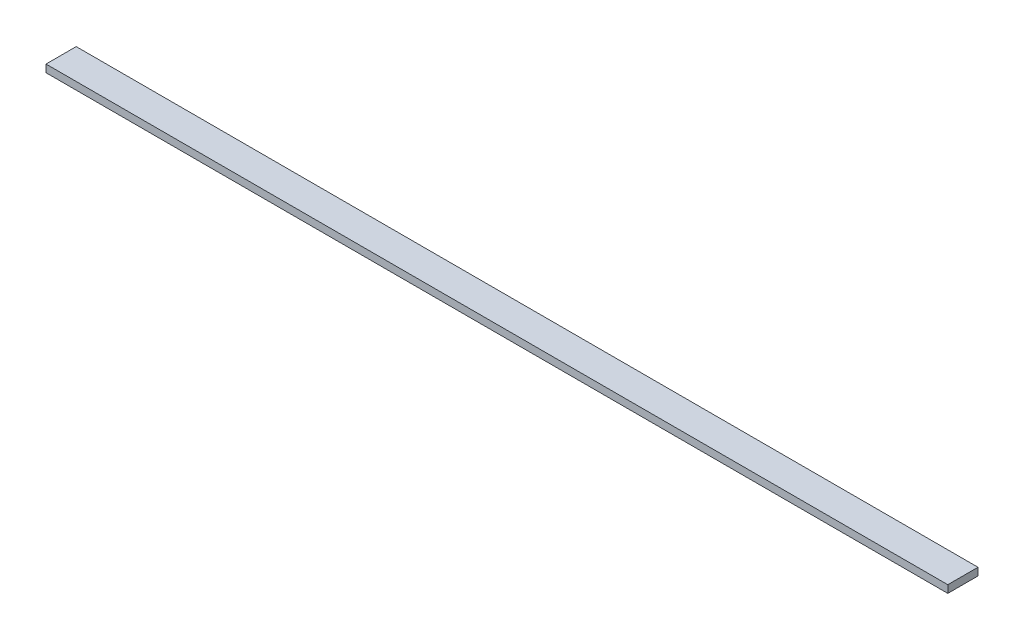
SolidWorks part; units mm, degrees
material "NEOPRENE"
ref_plane "Front Plane" through (0, 0, 0) normal (0, 0, 1) x (1, 0, 0)
ref_plane "Top Plane" through (0, 0, 0) normal (0, 1, 0) x (1, 0, 0)
ref_plane "Right Plane" through (0, 0, 0) normal (1, 0, 0) x (0, 0, -1)
sketch "Sketch1" plane through (0, 0, 0) normal (1, 0, 0) x (0, 0, -1)
  line L1 (-9.525, -2.3812) -> (9.525, -2.3812)
  line L2 (-9.525, -2.3812) -> (-9.525, 2.3813)
  line L3 (-9.525, 2.3813) -> (9.525, 2.3813)
  line L4 (9.525, -2.3812) -> (9.525, 2.3813)
  line L5 (-9.525, -2.3812) -> (9.525, 2.3813) construction
  line L6 (-9.525, 2.3813) -> (9.525, -2.3812) construction
  point P0 (0, 0)
  dimension "D1" = 4.7625
  dimension "D2" = 19.05
extrude "Boss-Extrude1" add sketch "Sketch1" along normal mid plane 568.75
